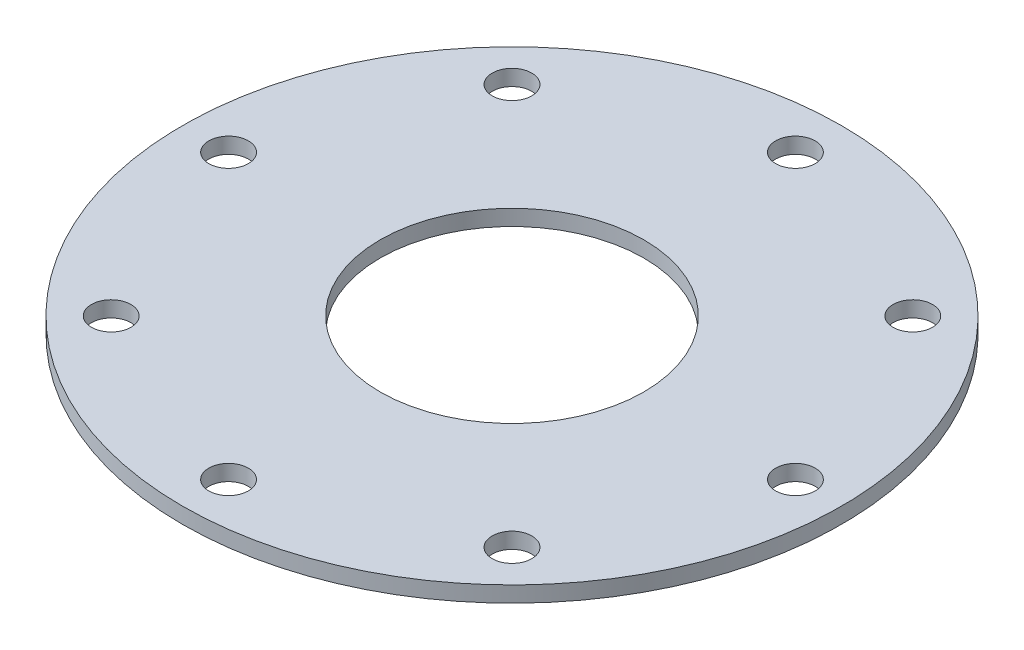
SolidWorks part; units mm, degrees
material "Plain Carbon Steel"
ref_plane "Front Plane" through (0, 0, 0) normal (0, 0, 1) x (1, 0, 0)
ref_plane "Top Plane" through (0, 0, 0) normal (0, 1, 0) x (1, 0, 0)
ref_plane "Right Plane" through (0, 0, 0) normal (1, 0, 0) x (0, 0, -1)
sketch "Sketch1" plane through (0, 0, 0) normal (0, 1, 0) x (1, 0, 0)
  circle A0 centre (0, 0) radius 125
  dimension "D1" = 250
extrude "Boss-Extrude1" add sketch "Sketch1" along normal blind 6
sketch "Sketch2" plane through (0, 6, 0) normal (0, 1, 0) x (1, 0, 0)
  circle A0 centre (0, 0) radius 50
  dimension "D1" = 100
extrude "Cut-Extrude1" cut sketch "Sketch2" against normal blind 6
sketch "Sketch3" plane through (0, 6, 0) normal (0, 1, 0) x (1, 0, 0)
  circle A0 centre (0, 0) radius 107.5 construction
  circle A1 centre (0, 107.5) radius 7.5
  dimension "D1" = 215
  dimension "D2" = 15
extrude "Cut-Extrude2" cut sketch "Sketch3" against normal blind 6
pattern_circular "CirPattern1" count 8 over 360 about axis through (0, 0, 0) along (0, 1, 0) of "Cut-Extrude2"
